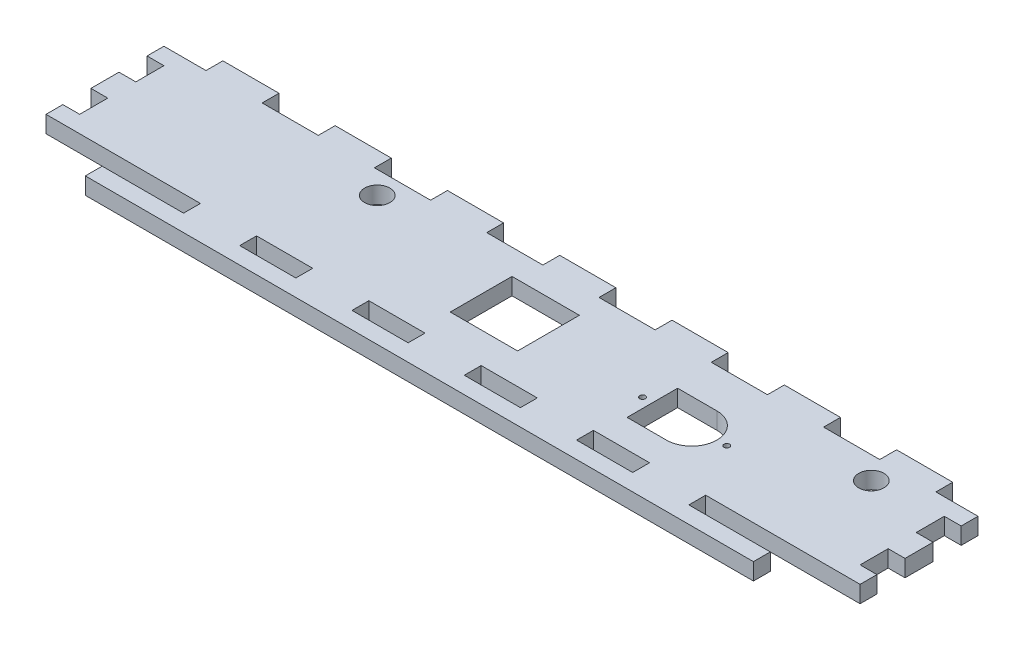
SolidWorks part; units mm, degrees
material "Maple"
ref_plane "Front Plane" through (0, 0, 0) normal (0, 0, 1) x (1, 0, 0)
ref_plane "Top Plane" through (0, 0, 0) normal (0, 1, 0) x (1, 0, 0)
ref_plane "Right Plane" through (0, 0, 0) normal (1, 0, 0) x (0, 0, -1)
sketch "Sketch1" plane through (0, 0, 0) normal (0, 1, 0) x (1, 0, 0)
  line L1 (0, 0) -> (145, 0)
  line L2 (0, 0) -> (0, -21)
  line L3 (0, -21) -> (145, -21)
  line L4 (145, 0) -> (145, -21)
  dimension "D1" = 145
  dimension "D2" = 21
extrude "Boss-Extrude1" add sketch "Sketch1" along normal blind 3
sketch "Sketch2" plane through (0, 3, 0) normal (0, 1, 0) x (1, 0, 0)
  line L0 (72.5, -21) -> (72.5, 0) construction
  line L1 (0, -21) -> (145, -21) construction
  line L2 (145, 0) -> (0, 0) construction
  line L4 (66.5, -4.5) -> (78.5, -4.5)
  line L5 (66.5, -4.5) -> (66.5, -15.5)
  line L6 (66.5, -15.5) -> (78.5, -15.5)
  line L7 (78.5, -4.5) -> (78.5, -15.5)
  line L8 (66.5, -4.5) -> (78.5, -15.5) construction
  line L9 (66.5, -15.5) -> (78.5, -4.5) construction
  point P6 (72.5, -10)
  dimension "D1" = 4.5
  dimension "D2" = 11
  dimension "D3" = 12
extrude "Cut-Extrude1" cut sketch "Sketch2" against normal through all
sketch "Sketch3" plane through (0, 3, 0) normal (0, 1, 0) x (1, 0, 0)
  line L0 (145, 0) -> (0, 0) construction
  line L1 (0, 0) -> (0, -21) construction
  line L3 (145, -21) -> (145, 0) construction
  circle A0 centre (42, -4) radius 2.25
  circle A1 centre (130, -4) radius 2.25
  dimension "D1" = 4.5
  dimension "D4" = 4.5
  dimension "D5" = 4
  dimension "D2" = 42
  dimension "D3" = 4
  dimension "D6" = 15
extrude "Cut-Extrude2" cut sketch "Sketch3" against normal through all
sketch "Sketch4" plane through (0, 3, 0) normal (0, 1, 0) x (1, 0, 0)
  line L0 (98.5, -11.5) -> (110, -11.5) construction
  line L1 (98.5, -16) -> (110, -16)
  line L2 (98.5, -16) -> (98.5, -7)
  line L3 (98.5, -7) -> (110, -7)
  line L4 (110, -16) -> (110, -7)
  line L5 (0, -21) -> (145, -21) construction
  line L6 (145, -21) -> (145, 0) construction
  line L7 (104.25, -16) -> (104.25, -7) construction
  circle A0 centre (105.5, -11.5) radius 4.5
  circle A1 centre (96.75, -11.5) radius 0.5
  circle A2 centre (111.75, -11.5) radius 0.5
  dimension "D5" = 1
  dimension "D6" = 1
  dimension "D1" = 9
  dimension "D2" = 11.5
  dimension "D3" = 5
  dimension "D4" = 35
  dimension "D7" = 15
  dimension "D8" = 7.5
extrude "Cut-Extrude3" cut sketch "Sketch4" against normal through all contours L0 A0 | A0 L3 L2 L1 | A1 | A2
sketch "Sketch5" plane through (0, 3, 0) normal (0, 1, 0) x (1, 0, 0)
  line L0 (72.5, 0) -> (72.5, -21) construction
  line L1 (145, 0) -> (0, 0) construction
  line L2 (0, -21) -> (145, -21) construction
  line L4 (67.5, -21) -> (77.5, -21)
  line L5 (67.5, -21) -> (67.5, -24)
  line L6 (67.5, -24) -> (77.5, -24)
  line L7 (77.5, -21) -> (77.5, -24)
  line L8 (67.5, -21) -> (77.5, -24) construction
  line L9 (67.5, -24) -> (77.5, -21) construction
  line L10 (67.5, 0) -> (77.5, 0)
  line L11 (67.5, 0) -> (67.5, 3)
  line L12 (67.5, 3) -> (77.5, 3)
  line L13 (77.5, 0) -> (77.5, 3)
  line L14 (67.5, 0) -> (77.5, 3) construction
  line L15 (67.5, 3) -> (77.5, 0) construction
  point P6 (72.5, -22.5)
  point P11 (72.5, 1.5)
  dimension "D1" = 3
  dimension "D2" = 3
  dimension "D3" = 10
extrude "Boss-Extrude2" add sketch "Sketch5" against normal through all
pattern_linear "LPattern1" count 4 spacing 20 along (-1, 0, 0) count 4 spacing 20 along (1, 0, 0) of "Boss-Extrude2"
sketch "Sketch6" plane through (0, 3, 0) normal (0, 1, 0) x (1, 0, 0)
  line L0 (7.5, -24) -> (17.5, -24) construction
  line L1 (0, -24) -> (145, -24)
  line L2 (0, -24) -> (0, -27)
  line L3 (0, -27) -> (145, -27)
  line L4 (145, -24) -> (145, -27)
  line L5 (0, 0) -> (0, -21) construction
  line L6 (145, -21) -> (145, 0) construction
  dimension "D1" = 3
extrude "Boss-Extrude3" add sketch "Sketch6" against normal through all
sketch "Sketch8" plane through (0, 0, 0) normal (0, -1, 0) x (-1, 0, 0)
  line L1 (-7.5, -24) -> (-17.5, -24)
  line L2 (-7.5, -24) -> (-7.5, -21)
  line L3 (-7.5, -21) -> (-17.5, -21)
  line L4 (-17.5, -24) -> (-17.5, -21)
  line L5 (-137.5, -24) -> (-127.5, -24)
  line L6 (-137.5, -24) -> (-137.5, -21)
  line L7 (-137.5, -21) -> (-127.5, -21)
  line L8 (-127.5, -24) -> (-127.5, -21)
extrude "Cut-Extrude4" cut sketch "Sketch8" against normal through all
sketch "Sketch9" plane through (0, 3, 0) normal (0, 1, 0) x (1, 0, 0)
  line L0 (0, 0) -> (0, -21) construction
  line L1 (3, -13) -> (0, -13)
  line L2 (3, -13) -> (3, -18)
  line L3 (3, -18) -> (0, -18)
  line L4 (0, -13) -> (0, -18)
  line L5 (0, 0) -> (0, -21) construction
  line L6 (145, -21) -> (145, 0) construction
  line L7 (3, -3) -> (0, -3)
  line L8 (3, -3) -> (3, -8)
  line L9 (3, -8) -> (0, -8)
  line L10 (0, -3) -> (0, -8)
  line L11 (142, -13) -> (145, -13)
  line L12 (142, -13) -> (142, -18)
  line L13 (142, -18) -> (145, -18)
  line L14 (145, -13) -> (145, -18)
  line L15 (7.5, 0) -> (0, 0) construction
  line L16 (142, -3) -> (145, -3)
  line L17 (142, -3) -> (142, -8)
  line L18 (142, -8) -> (145, -8)
  line L19 (145, -3) -> (145, -8)
  dimension "D1" = 3
  dimension "D2" = 5
  dimension "D3" = 5
  dimension "D4" = 5
  dimension "D5" = 3
extrude "Cut-Extrude5" cut sketch "Sketch9" against normal through all
sketch "Sketch10" plane through (0, 0, 0) normal (0, -1, 0) x (-1, 0, 0)
  line L0 (-27.5, -24) -> (0, -24) construction
  line L1 (0, -27) -> (-13, -27)
  line L2 (0, -27) -> (0, -24)
  line L3 (0, -24) -> (-13, -24)
  line L4 (-13, -27) -> (-13, -24)
  line L5 (-145, -24) -> (-117.5, -24) construction
  line L6 (-145, -27) -> (-132, -27)
  line L7 (-145, -27) -> (-145, -24)
  line L8 (-145, -24) -> (-132, -24)
  line L9 (-132, -27) -> (-132, -24)
  dimension "D1" = 13
extrude "Cut-Extrude6" cut sketch "Sketch10" against normal through all
equation "\"D6@Sketch4\"=\"D5@Sketch4\""
equation "\"D8@Sketch4\"=\"D7@Sketch4\"/2"
